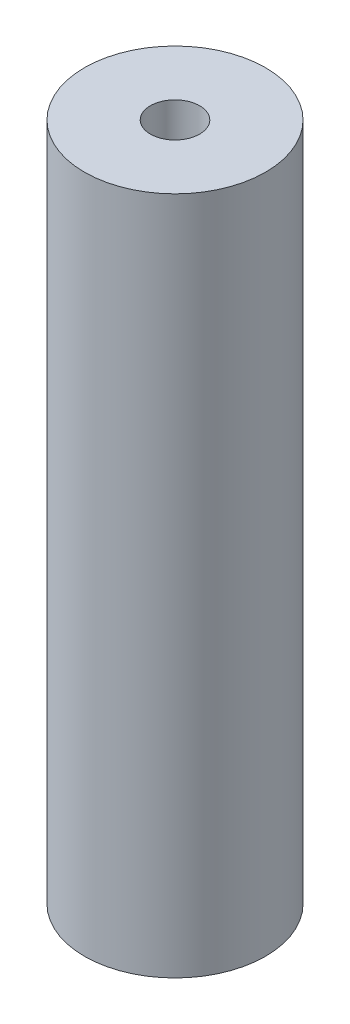
SolidWorks part; units mm, degrees
material "PE High Density"
ref_plane "Front" through (0, 0, 0) normal (0, 0, 1) x (1, 0, 0)
ref_plane "Top" through (0, 0, 0) normal (0, 1, 0) x (1, 0, 0)
ref_plane "Right" through (0, 0, 0) normal (1, 0, 0) x (0, 0, -1)
sketch "Sketch1" plane through (0, 0, 0) normal (0, 1, 0) x (1, 0, 0)
  circle A0 centre (0, 0) radius 6.35
  circle A1 centre (0, 0) radius 1.7272
  dimension "D1" = 12.7
  dimension "D2" = 3.4544
extrude "Boss-Extrude1" add sketch "Sketch1" along normal mid plane 47.625 contours A0
